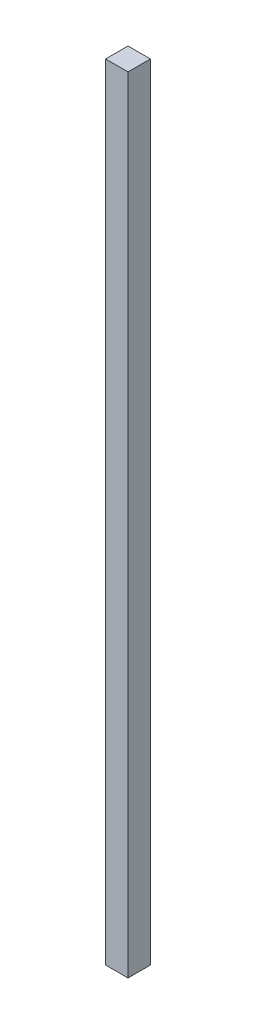
SolidWorks part; units mm, degrees
ref_plane "Plan de face" through (0, 0, 0) normal (0, 0, 1) x (1, 0, 0)
ref_plane "Plan de dessus" through (0, 0, 0) normal (0, 1, 0) x (1, 0, 0)
ref_plane "Plan de droite" through (0, 0, 0) normal (1, 0, 0) x (0, 0, -1)
sketch "Esquisse1" plane through (0, 0, 0) normal (0, 1, 0) x (1, 0, 0)
  line L0 (-5, 5) -> (5, -5) construction
  line L1 (-5, 5) -> (5, 5)
  line L2 (-5, 5) -> (-5, -5)
  line L3 (-5, -5) -> (5, -5)
  line L4 (5, 5) -> (5, -5)
  point P5 (-4.6877, 6.6472)
  dimension "D1" = 10
extrude "Boss.-Extru.1" add sketch "Esquisse1" along normal blind 350
